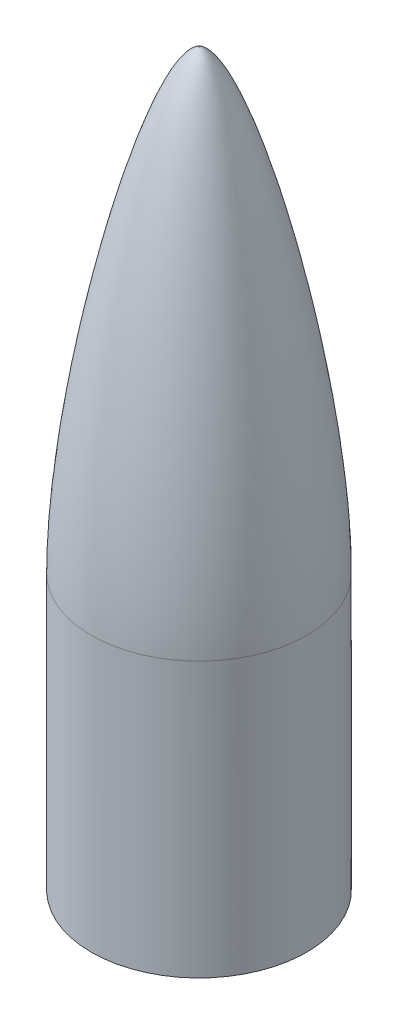
SolidWorks part; units mm, degrees
ref_plane "Front Plane" through (0, 0, 0) normal (0, 0, 1) x (1, 0, 0)
ref_plane "Top Plane" through (0, 0, 0) normal (0, 1, 0) x (1, 0, 0)
ref_plane "Right Plane" through (0, 0, 0) normal (1, 0, 0) x (0, 0, -1)
sketch "Sketch2" plane through (0, 0, 0) normal (0, 0, 1) x (1, 0, 0)
  line L0 (0, -124.3397) -> (0, 6092.6457) construction
  line L1 (-2.85, 0) -> (2.85, 0) construction
  line L2 (-2.85, 19.3) -> (2.85, 19.3) construction
  line L3 (2.85, 0) -> (2.85, 7.2571)
  line L4 (2.85, 0) -> (0, 0)
  line L5 (0, 0) -> (0, 19.3)
  line L6 (2.85, 2.1471) -> (2.85, 12.3672) construction
  spline S0 degree 3 poles (0, 19.3) (1.018, 19.1229) (2.85, 11.5155) (2.85, 7.2571) knots 0 0 0 0 1 1 1 1
  point P5 (0, 0)
  dimension "D1" = 5.7
  dimension "D2" = 19.3
revolve "Revolve1" add sketch "Sketch2" angle 360 about L5
